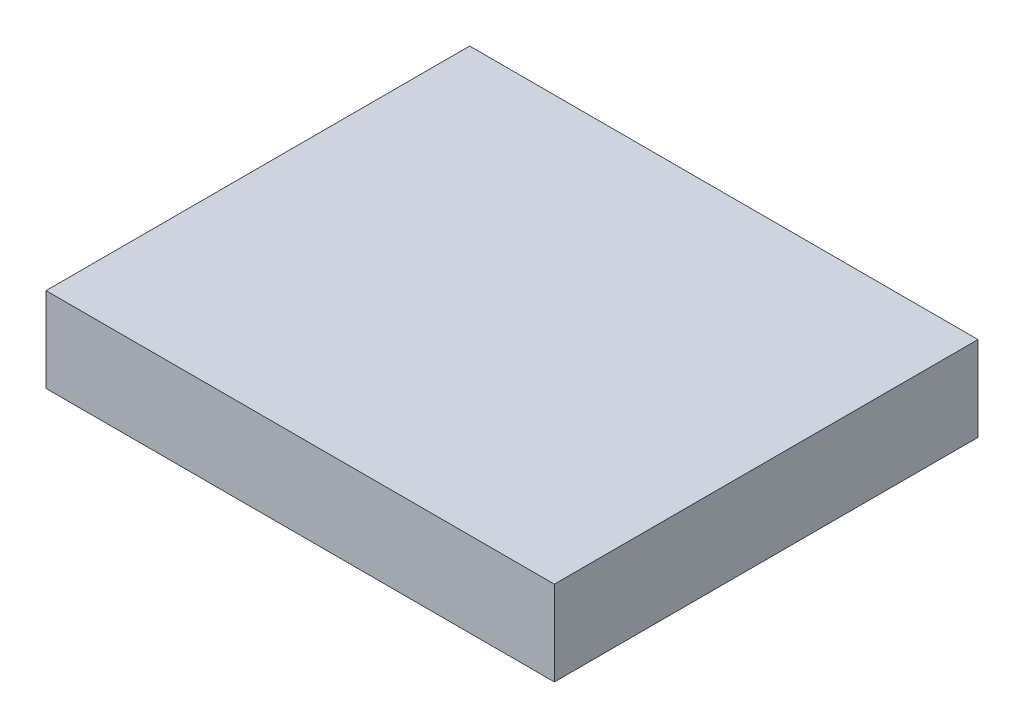
SolidWorks part; units mm, degrees
ref_plane "Front Plane" through (0, 0, 0) normal (0, 0, 1) x (1, 0, 0)
ref_plane "Top Plane" through (0, 0, 0) normal (0, 1, 0) x (1, 0, 0)
ref_plane "Right Plane" through (0, 0, 0) normal (1, 0, 0) x (0, 0, -1)
sketch "Sketch2" plane through (0, 0, 0) normal (0, 1, 0) x (1, 0, 0)
  line L1 (0, 0) -> (38.1, 0)
  line L2 (0, 0) -> (0, 31.75)
  line L3 (0, 31.75) -> (38.1, 31.75)
  line L12 (38.1, 31.75) -> (38.1, 0)
  dimension "D1" = 38.1
  dimension "D2" = 31.75
extrude "Boss-Extrude1" add sketch "Sketch2" along normal blind 6.35
